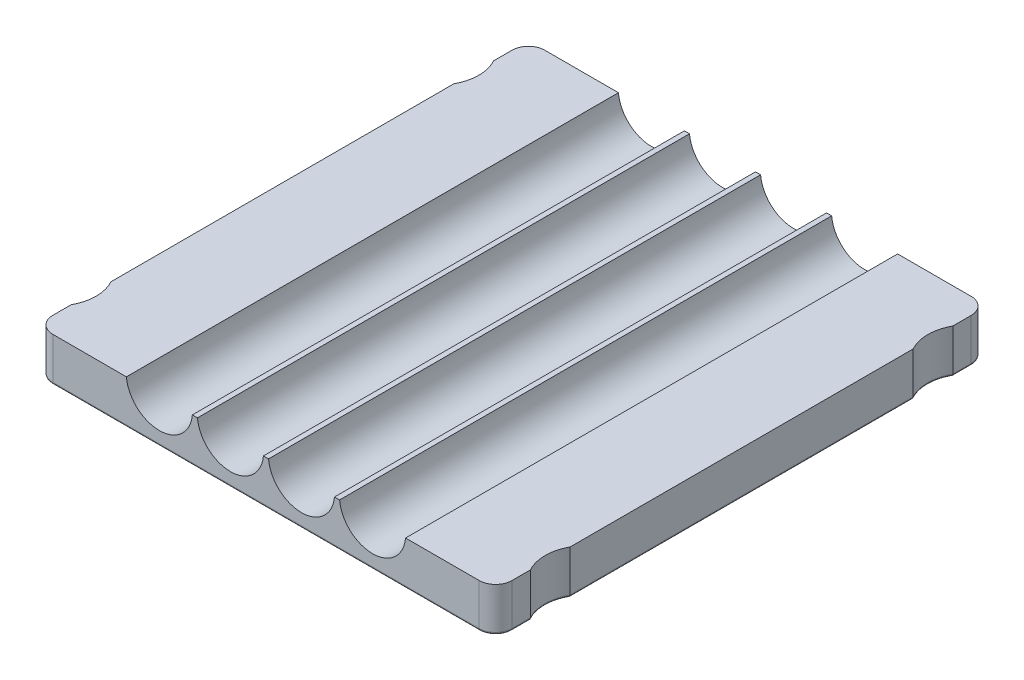
SolidWorks part; units mm, degrees
ref_plane "Front" through (0, 0, 0) normal (0, 0, 1) x (1, 0, 0)
ref_plane "Top" through (0, 0, 0) normal (0, 1, 0) x (1, 0, 0)
ref_plane "Right" through (0, 0, 0) normal (1, 0, 0) x (0, 0, -1)
sketch "Sketch1" plane through (0, 0, 0) normal (0, 1, 0) x (1, 0, 0)
  line L0 (-16.5, 17.5) -> (16.5, -17.5) construction
  line L714 (-19, 17.5) -> (-19, -17.5)
  line L726 (-16.5, -20) -> (16.5, -20)
  line L988 (19, -17.5) -> (19, 17.5)
  line L1035 (16.5, 20) -> (-16.5, 20)
  arc A87 (-19, -17.5) -> (-16.5, -20) centre (-16.5, -17.5) ccw
  arc A108 (-16.5, 20) -> (-19, 17.5) centre (-16.5, 17.5) ccw
  arc A131 (16.5, -20) -> (19, -17.5) centre (16.5, -17.5) ccw
  arc A151 (19, 17.5) -> (16.5, 20) centre (16.5, 17.5) ccw
extrude "Boss-Extrude1" add sketch "Sketch1" along normal blind 0.5
sketch "Sketch2" plane through (0, 0.5, 0) normal (0, 1, 0) x (1, 0, 0)
  line L0 (-16.5, 17.5) -> (16.5, -17.5) construction
  line L1 (-19.5, 22.5) -> (19.5, 22.5)
  line L2 (-19.5, -22.5) -> (19.5, -22.5)
  line L698 (-21, 21) -> (-21, 19.3141)
  line L699 (-21, 15.6859) -> (-21, -15.6859)
  line L700 (-21, -19.3141) -> (-21, -21)
  line L1002 (21, -21) -> (21, -19.3141)
  line L1003 (21, -15.6859) -> (21, 15.6859)
  line L1004 (21, 19.3141) -> (21, 21)
  arc A83 (-21, -19.3141) -> (-21, -15.6859) centre (-24.282, -17.5) ccw
  arc A85 (-21, -21) -> (-19.5, -22.5) centre (-19.5, -21) ccw
  arc A100 (-21, 15.6859) -> (-21, 19.3141) centre (-24.282, 17.5) ccw
  arc A102 (-19.5, 22.5) -> (-21, 21) centre (-19.5, 21) ccw
  arc A135 (21, -15.6859) -> (21, -19.3141) centre (24.282, -17.5) ccw
  arc A137 (19.5, -22.5) -> (21, -21) centre (19.5, -21) ccw
  arc A154 (21, 19.3141) -> (21, 15.6859) centre (24.282, 17.5) ccw
  arc A156 (21, 21) -> (19.5, 22.5) centre (19.5, 21) ccw
extrude "Boss-Extrude2" add sketch "Sketch2" along normal blind 4
fillet "Fillet1" radius 0.2 24 edges at (0, 0, 20) (18.2678, 0, 19.2678) (19, 0, 0) (18.2678, 0, -19.2678) (0, 0, -20) (-18.2678, 0, -19.2678) (-19, 0, 0) (-18.2678, 0, 19.2678) (21, 0.5, -20.1571) (20.5607, 0.5, -22.0607) (0, 0.5, -22.5) (-20.5607, 0.5, -22.0607) (-21, 0.5, 20.1571) (-20.5607, 0.5, 22.0607) (21, 0.5, 20.1571) (20.5607, 0.5, 22.0607) (20.532, 0.5, 17.5) (21, 0.5, 0) (20.532, 0.5, -17.5) (-21, 0.5, -20.1571) (-20.532, 0.5, -17.5) (-21, 0.5, 0) (-20.532, 0.5, 17.5) (0, 0.5, 22.5)
sketch "Sketch3" plane through (0, 0, 0) normal (0, 0, 1) x (1, 0, 0)
  arc A0 (12.7791, 4.705) -> (6.7209, 4.705) centre (9.75, 4.78) ccw construction
  arc A1 (6.2791, 4.705) -> (0.2209, 4.705) centre (3.25, 4.78) ccw construction
  arc A2 (-0.2209, 4.705) -> (-6.2791, 4.705) centre (-3.25, 4.78) ccw construction
  arc A3 (-6.7209, 4.705) -> (-12.7791, 4.705) centre (-9.75, 4.78) ccw construction
  circle A4 centre (9.75, 4.78) radius 3.03
  circle A5 centre (3.25, 4.78) radius 3.03
  circle A6 centre (-3.25, 4.78) radius 3.03
  circle A7 centre (-9.75, 4.78) radius 3.03
extrude "Cut-Extrude1" cut sketch "Sketch3" against normal through all both and the other way through all
